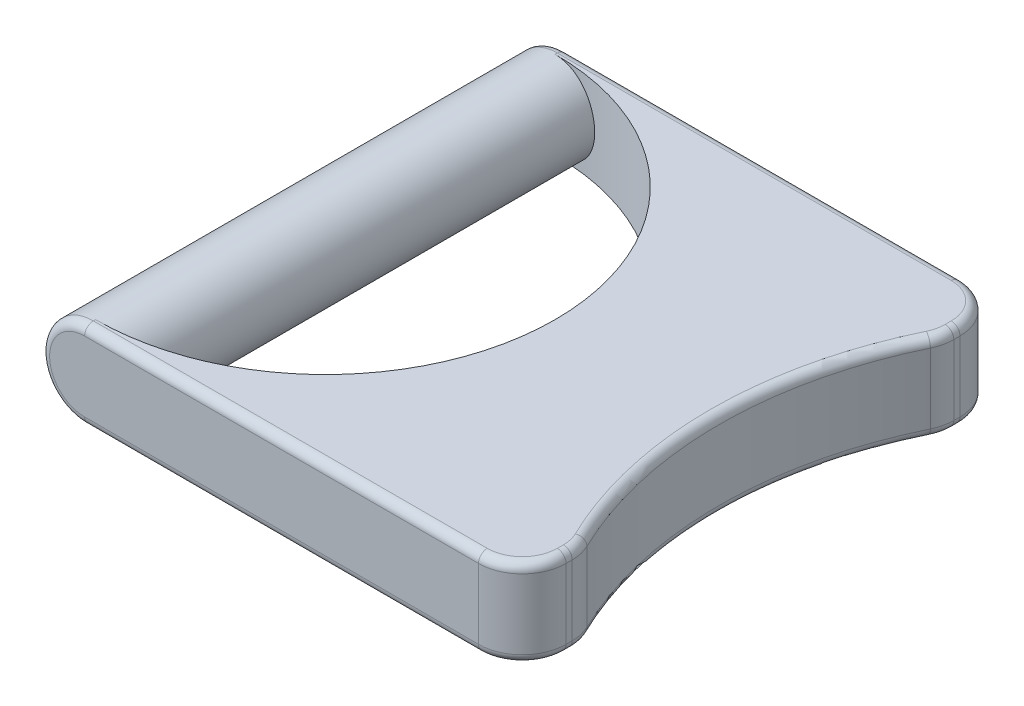
SolidWorks part; units mm, degrees
ref_plane "Front Plane" through (0, 0, 0) normal (0, 0, 1) x (1, 0, 0)
ref_plane "Top Plane" through (0, 0, 0) normal (0, 1, 0) x (1, 0, 0)
ref_plane "Right Plane" through (0, 0, 0) normal (1, 0, 0) x (0, 0, -1)
sketch "Sketch1" plane through (0, 0, 0) normal (0, 0, 1) x (1, 0, 0)
  circle A0 centre (0, 0) radius 1
  dimension "D1" = 2
extrude "Boss-Extrude1" add sketch "Sketch1" along normal mid plane 11
sketch "Sketch2" plane through (0, 0, 0) normal (0, 1, 0) x (1, 0, 0)
  line L0 (0, 5.5) -> (9, 5.5)
  line L1 (1, 5.5) -> (-1, 5.5) construction
  line L3 (9, -5.5) -> (0, -5.5)
  line L4 (-1, -5.5) -> (1, -5.5) construction
  line L5 (0, -5.5) -> (0, -5.25)
  line L6 (0, 5.25) -> (0, 5.5)
  line L8 (10, 4.5) -> (10, 4.3589)
  line L9 (10, -4.3589) -> (10, -4.5)
  arc A0 (0, -5.25) -> (0, 5.25) centre (0, 0) ccw
  arc A1 (9.9, 3.923) -> (9.9, -3.923) centre (18, 0) ccw
  arc A2 (10, -4.5) -> (9, -5.5) centre (9, -4.5) cw
  arc A3 (9, 5.5) -> (10, 4.5) centre (9, 4.5) cw
  arc A4 (10, -4.3589) -> (9.9, -3.923) centre (9, -4.3589) ccw
  arc A5 (10, 4.3589) -> (9.9, 3.923) centre (9, 4.3589) cw
  point P20 (10, 5.5)
  dimension "D1" = 10.5
  dimension "D3" = 18
  dimension "D5" = 1
  dimension "D6" = 1
  dimension "D2" = 10
  dimension "D4" = 18
extrude "Boss-Extrude2" add sketch "Sketch2" along normal mid plane 2
fillet "Fillet1" radius 0.2 20 edges at (-1, 0, 5.5) (4.5, -1, 5.5) (9.7071, -1, 5.2071) (10, -1, 4.4294) (9.9747, -1, 4.1353) (9, -1, 0) (9.9747, -1, -4.1353) (10, -1, -4.4294) (9.7071, -1, -5.2071) (4.5, -1, -5.5) (-1, 0, -5.5) (4.5, 1, -5.5) (9.7071, 1, -5.2071) (10, 1, -4.4294) (9.9747, 1, -4.1353) (9, 1, 0) (9.9747, 1, 4.1353) (10, 1, 4.4294) (9.7071, 1, 5.2071) (4.5, 1, 5.5)
